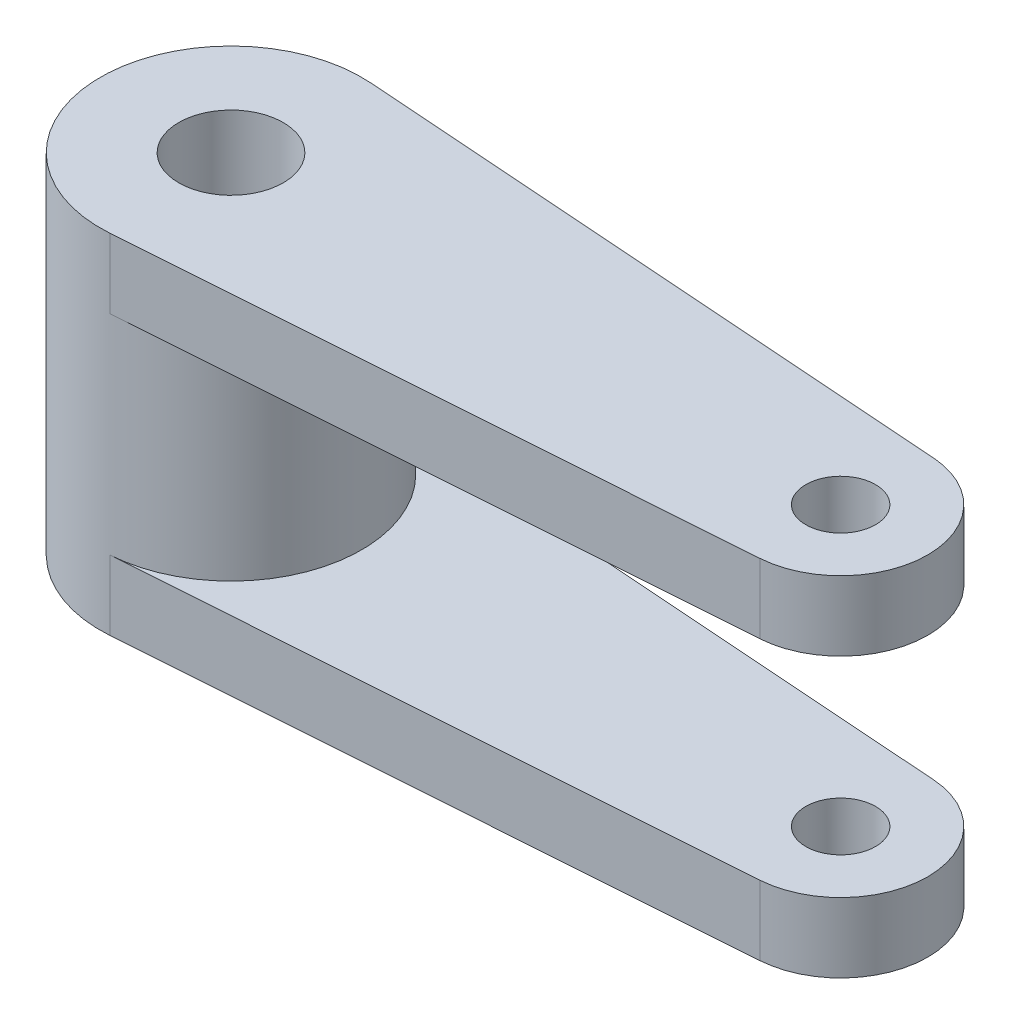
SolidWorks part; units mm, degrees
ref_plane "前视基准面" through (0, 0, 0) normal (0, 0, 1) x (1, 0, 0)
ref_plane "上视基准面" through (0, 0, 0) normal (0, 1, 0) x (1, 0, 0)
ref_plane "右视基准面" through (0, 0, 0) normal (1, 0, 0) x (0, 0, -1)
ref_plane "基准面1" through (0, -20, 0) normal (0, 1, 0) x (1, 0, 0)
sketch "草图1" plane through (0, -20, 0) normal (0, 1, 0) x (1, 0, 0)
  circle A0 centre (0, 0) radius 15
extrude "凸台-拉伸1" add sketch "草图1" along normal blind 40
sketch "草图2" plane through (0, -20, 0) normal (0, 1, 0) x (1, 0, 0)
  line L0 (1.0714, 14.9617) -> (70.7143, 9.9745)
  line L1 (70.7143, -9.9745) -> (1.0714, -14.9617)
  arc A0 (70.7143, 9.9745) -> (70.7143, -9.9745) centre (70, 0) cw
  arc A1 (1.0714, -14.9617) -> (1.0714, 14.9617) centre (0, 0) cw
extrude "凸台-拉伸2" add sketch "草图2" along normal blind 8
mirror "镜向1" about plane through (0, 0, 0) normal (0, 1, 0) of "凸台-拉伸2"
sketch "草图3" plane through (0, 0, 0) normal (0, 1, 0) x (1, 0, 0)
  circle A0 centre (0, 0) radius 6
extrude "切除-拉伸1" cut sketch "草图3" against normal mid plane 192
sketch "草图4" plane through (0, 0, 0) normal (0, 1, 0) x (1, 0, 0)
  circle A0 centre (70, 0) radius 4
extrude "切除-拉伸2" cut sketch "草图4" against normal mid plane 192
